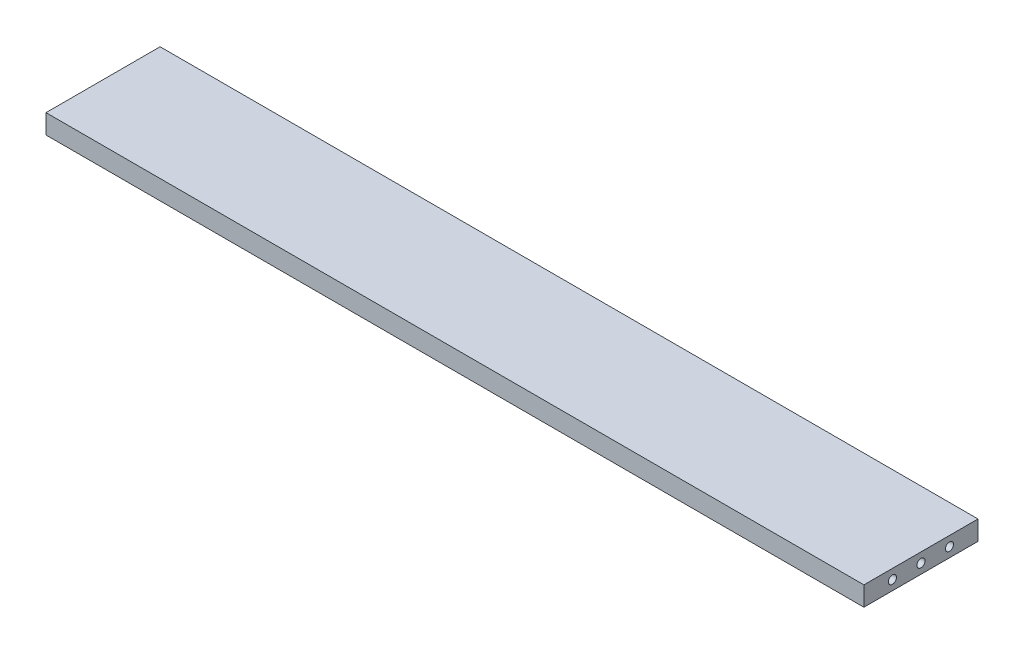
SolidWorks part; units mm, degrees
ref_plane "Plano frontal" through (0, 0, 0) normal (0, 0, 1) x (1, 0, 0)
ref_plane "Plano superior" through (0, 0, 0) normal (0, 1, 0) x (1, 0, 0)
ref_plane "Plano direito" through (0, 0, 0) normal (1, 0, 0) x (0, 0, -1)
sketch "Esboço1" plane through (0, 0, 0) normal (0, 1, 0) x (1, 0, 0)
  line L0 (200.715, 28) -> (-200.715, -28) construction
  line L1 (-200.715, 28) -> (200.715, 28)
  line L2 (-200.715, 28) -> (-200.715, -28)
  line L3 (-200.715, -28) -> (200.715, -28)
  line L4 (200.715, 28) -> (200.715, -28)
  line L5 (-200.715, -28) -> (-200.707, -28.2845) construction
  dimension "D1" = 401.43
  dimension "D2" = 56
extrude "Ressalto-extrusão1" add sketch "Esboço1" along normal blind 9.525
sketch "Esboço2" plane through (200.715, 0, 0) normal (1, 0, 0) x (0, 0, -1)
  line L0 (-28, 4.7625) -> (28, 4.7625) construction
  line L1 (-28, 9.525) -> (-28, 0) construction
  line L2 (28, 9.525) -> (28, 0) construction
  circle A0 centre (-14, 4.7625) radius 2
  circle A1 centre (0, 4.7625) radius 2
  circle A2 centre (14, 4.7625) radius 2
  dimension "D1" = 4
  dimension "D2" = 4
  dimension "D3" = 4
  dimension "D4" = 14
  dimension "D5" = 14
extrude "Corte-extrusão1" cut sketch "Esboço2" against normal blind 30
sketch "Esboço3" plane through (-200.715, 0, 0) normal (-1, 0, 0) x (0, 0, 1)
  line L0 (-28, 4.7625) -> (28, 4.7625) construction
  line L1 (-28, 9.525) -> (-28, 0) construction
  line L2 (28, 9.525) -> (28, 0) construction
  circle A0 centre (-14, 4.7625) radius 2
  circle A1 centre (0, 4.7625) radius 2
  circle A2 centre (14, 4.7625) radius 2
  dimension "D2" = 4
  dimension "D3" = 4
  dimension "D5" = 4
  dimension "D1" = 14
  dimension "D4" = 14
extrude "Corte-extrusão2" cut sketch "Esboço3" against normal blind 20
